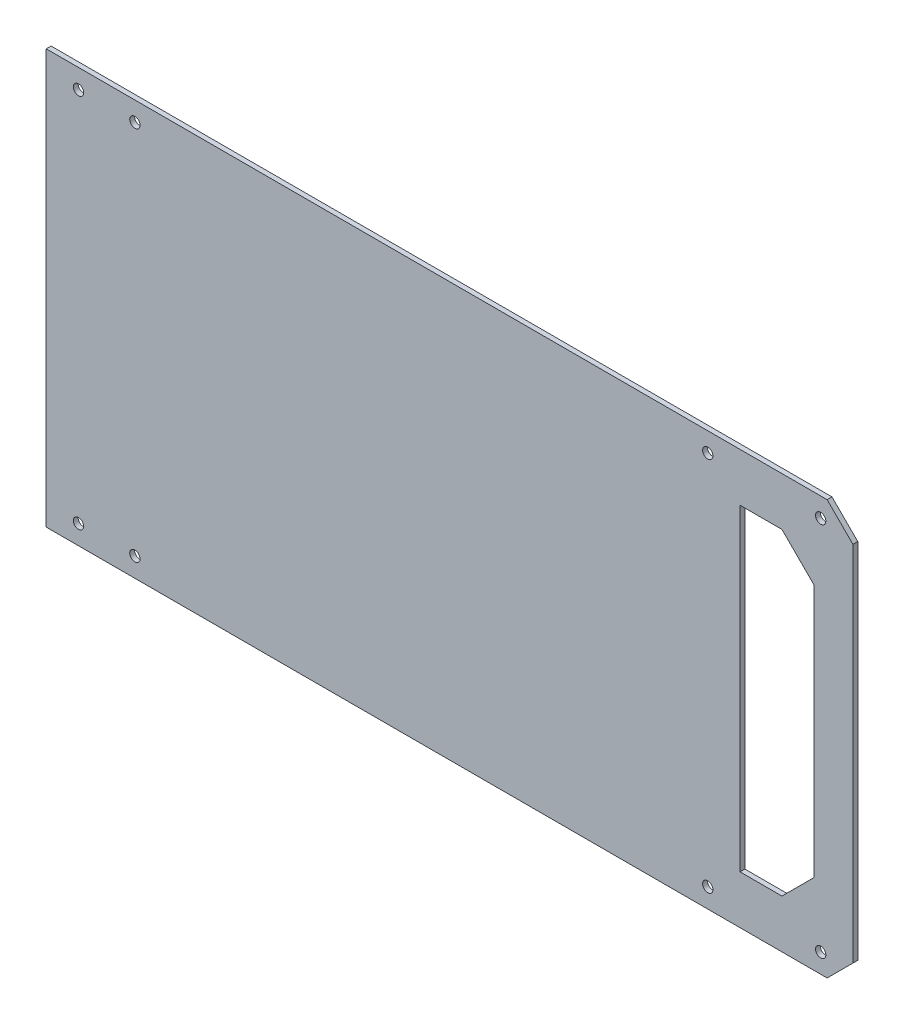
SolidWorks part; units mm, degrees
ref_plane "Front Plane" through (0, 0, 0) normal (0, 0, 1) x (1, 0, 0)
ref_plane "Top Plane" through (0, 0, 0) normal (0, 1, 0) x (1, 0, 0)
ref_plane "Right Plane" through (0, 0, 0) normal (1, 0, 0) x (0, 0, -1)
sketch "Sketch1" plane through (0, 0, 0) normal (0, 0, 1) x (1, 0, 0)
  line L0 (-613.414, 4.5) -> (-600.414, 4.5) construction
  line L1 (-600.414, 4.5) -> (-590.414, 14.5) construction
  line L2 (-590.414, 14.5) -> (-590.414, 92.9147) construction
  line L3 (-590.414, 92.9147) -> (-600.414, 102.9147) construction
  line L4 (-613.414, 102.9147) -> (-613.414, 4.5) construction
  line L5 (-600.414, 102.9147) -> (-613.414, 102.9147) construction
  line L6 (-798.4778, -10.5) -> (-798.4778, 24.6782)
  line L7 (-803.3395, 33.6467) -> (-806.4778, 33.6467)
  line L8 (-798.4778, 109.1466) -> (-798.4778, 117.9147)
  line L9 (-798.4778, 117.9147) -> (-828.4778, 117.9147)
  line L10 (-828.4778, 117.9147) -> (-828.4778, -10.5)
  line L11 (-828.4778, -10.5) -> (-798.4778, -10.5)
  line L15 (-586.414, 117.9147) -> (-828.4778, 117.9147)
  line L16 (-828.4778, 117.9147) -> (-828.4778, -10.5)
  line L17 (-828.4778, -10.5) -> (-586.414, -10.5)
  line L18 (-627.4379, 117.9147) -> (-627.4379, -10.5)
  line L19 (-627.4379, -10.5) -> (-586.414, -10.5)
  line L20 (-586.414, -10.5) -> (-578.414, -2.5)
  line L21 (-578.414, -2.5) -> (-578.414, 109.9147)
  line L22 (-578.414, 109.9147) -> (-586.414, 117.9147)
  line L23 (-586.414, 117.9147) -> (-627.4379, 117.9147)
  line L26 (-586.414, -10.5) -> (-578.414, -2.5)
  line L27 (-578.414, -2.5) -> (-578.414, 109.9147)
  line L28 (-578.414, 109.9147) -> (-586.414, 117.9147)
  line L30 (-613.414, 4.5) -> (-600.414, 4.5)
  line L31 (-600.414, 4.5) -> (-590.414, 14.5)
  line L32 (-590.414, 14.5) -> (-590.414, 92.9147)
  line L33 (-590.414, 92.9147) -> (-600.414, 102.9147)
  line L34 (-613.414, 102.9147) -> (-613.414, 4.5)
  line L35 (-600.414, 102.9147) -> (-613.414, 102.9147)
  line L62 (-803.3395, 29.5285) -> (-803.3395, 33.6467)
  line L64 (-803.3395, 100.1783) -> (-803.3395, 104.2849)
  line L275 (-806.4778, 33.6467) -> (-806.4778, 100.1783)
  line L277 (-806.4778, 100.1783) -> (-803.3395, 100.1783)
  arc A2 (-803.3395, 29.5285) -> (-798.4778, 24.6782) centre (-798.8544, 29.1624) ccw
  arc A8 (-798.4778, 109.1466) -> (-803.3395, 104.2849) centre (-798.8553, 104.6624) ccw
  dimension "D1" = 0
  dimension "D2" = 0
extrude "Boss-Extrude1" add sketch "Sketch1" along normal blind 1.5
sketch "Sketch2" plane through (0, 0, 1.5) normal (0, 0, 1) x (1, 0, 0)
  line L1 (-588.414, 111.9147) -> (-818.4778, 111.9147) construction
  line L2 (-588.414, 111.9147) -> (-588.414, -4.5) construction
  line L3 (-588.414, -4.5) -> (-818.4778, -4.5) construction
  line L4 (-818.4778, 111.9147) -> (-818.4778, -4.5) construction
  line L5 (-623.414, 111.9147) -> (-800.9925, 111.9147) construction
  line L6 (-623.414, 111.9147) -> (-623.414, -4.5) construction
  line L7 (-623.414, -4.5) -> (-800.9925, -4.5) construction
  line L8 (-800.9925, 111.9147) -> (-800.9925, -4.5) construction
  circle A0 centre (-818.4778, -4.5) radius 1.6 construction
  circle A1 centre (-800.9925, -4.5) radius 1.6 construction
  circle A2 centre (-623.414, -4.5) radius 1.6 construction
  circle A3 centre (-588.414, -4.5) radius 1.6 construction
  circle A4 centre (-623.414, 111.9147) radius 1.6 construction
  circle A5 centre (-588.414, 111.9147) radius 1.6 construction
  circle A6 centre (-818.4778, -4.5) radius 1.6
  circle A7 centre (-800.9925, -4.5) radius 1.6
  circle A8 centre (-623.414, -4.5) radius 1.6
  circle A9 centre (-588.414, -4.5) radius 1.6
  circle A10 centre (-623.414, 111.9147) radius 1.6
  circle A11 centre (-588.414, 111.9147) radius 1.6
  circle A12 centre (-818.4778, 111.9147) radius 1.6
  circle A13 centre (-800.9925, 111.9147) radius 1.6
extrude "Cut-Extrude1" cut sketch "Sketch2" against normal blind 3.5
